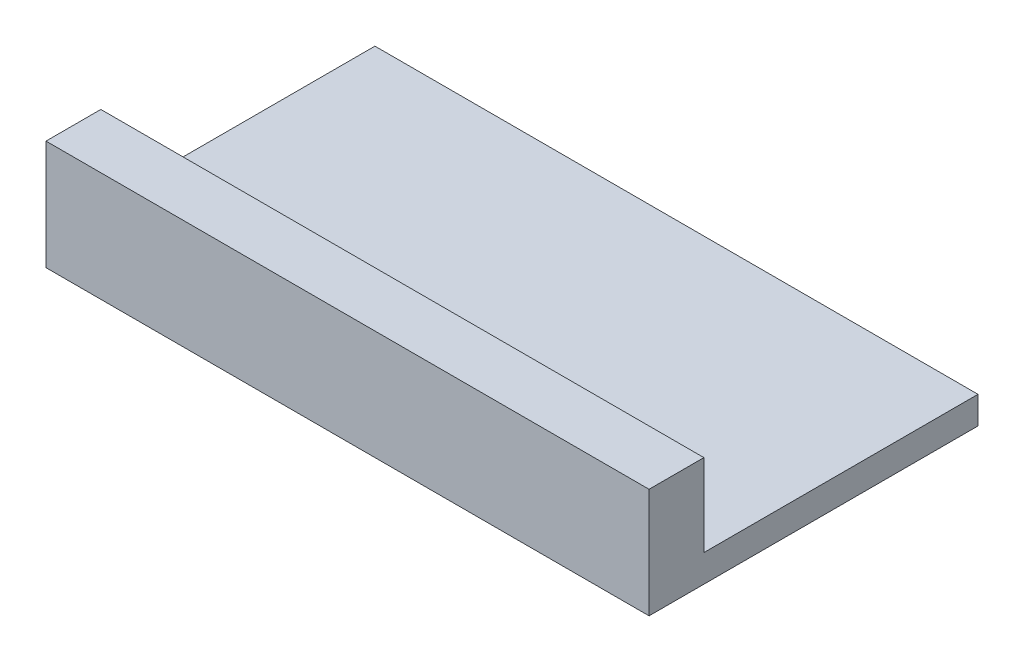
SolidWorks part; units mm, degrees
ref_plane "Front Plane" through (0, 0, 0) normal (0, 0, 1) x (1, 0, 0)
ref_plane "Top Plane" through (0, 0, 0) normal (0, 1, 0) x (1, 0, 0)
ref_plane "Right Plane" through (0, 0, 0) normal (1, 0, 0) x (0, 0, -1)
sketch "Sketch1" plane through (0, 0, 0) normal (0, 1, 0) x (1, 0, 0)
  line L0 (-69.85, -38.1) -> (69.85, -38.1)
  line L1 (-69.85, -38.1) -> (-69.85, 38.1)
  line L2 (69.85, -38.1) -> (69.85, 38.1)
  line L3 (-69.85, 38.1) -> (69.85, 38.1)
  line L4 (-69.85, -38.1) -> (69.85, 38.1) construction
  line L5 (69.85, -38.1) -> (-69.85, 38.1) construction
  point P1 (0, 0)
  dimension "D1" = 76.2
  dimension "D2" = 139.7
extrude "Boss-Extrude1" add sketch "Sketch1" along normal blind 6.35
sketch "Sketch2" plane through (0, 6.35, 0) normal (0, 1, 0) x (1, 0, 0)
  line L0 (-69.85, 38.1) -> (-69.85, -38.1) construction
  line L1 (-69.85, -38.1) -> (69.85, -38.1)
  line L2 (69.85, -38.1) -> (69.85, -25.4)
  line L3 (69.85, -38.1) -> (69.85, 38.1) construction
  line L4 (69.85, -25.4) -> (-69.85, -25.4)
  line L5 (-69.85, -25.4) -> (-69.85, -38.1)
  dimension "D2" = 12.7
extrude "Boss-Extrude2" add sketch "Sketch2" along normal blind 19.05
sketch "Sketch3" plane through (0, 6.35, 0) normal (0, 1, 0) x (1, 0, 0)
  line L1 (-69.85, -38.1) -> (69.85, -38.1) construction
  line L2 (-69.85, 38.1) -> (-69.85, -25.4) construction
  circle A0 centre (-53.34, -21.59) radius 2.032
  dimension "D1" = 4.064
  dimension "D2" = 16.51
  dimension "D3" = 16.51
extrude "Cut-Extrude1" cut sketch "Sketch3" against normal through all
sketch "Sketch4" plane through (0, 0, 0) normal (0, -1, 0) x (1, 0, 0)
  line L0 (-69.85, 38.1) -> (69.85, 38.1) construction
  line L1 (-50.927, 25.7694) -> (-55.753, 25.7694)
  line L2 (-55.753, 25.7694) -> (-58.166, 21.59)
  line L3 (-58.166, 21.59) -> (-55.753, 17.4106)
  line L4 (-55.753, 17.4106) -> (-50.927, 17.4106)
  line L5 (-50.927, 17.4106) -> (-48.514, 21.59)
  line L6 (-48.514, 21.59) -> (-50.927, 25.7694)
  circle A0 centre (-53.34, 21.59) radius 4.1794 construction
  dimension "D1" = 4.826
extrude "Cut-Extrude2" cut sketch "Sketch4" against normal blind 3.048
